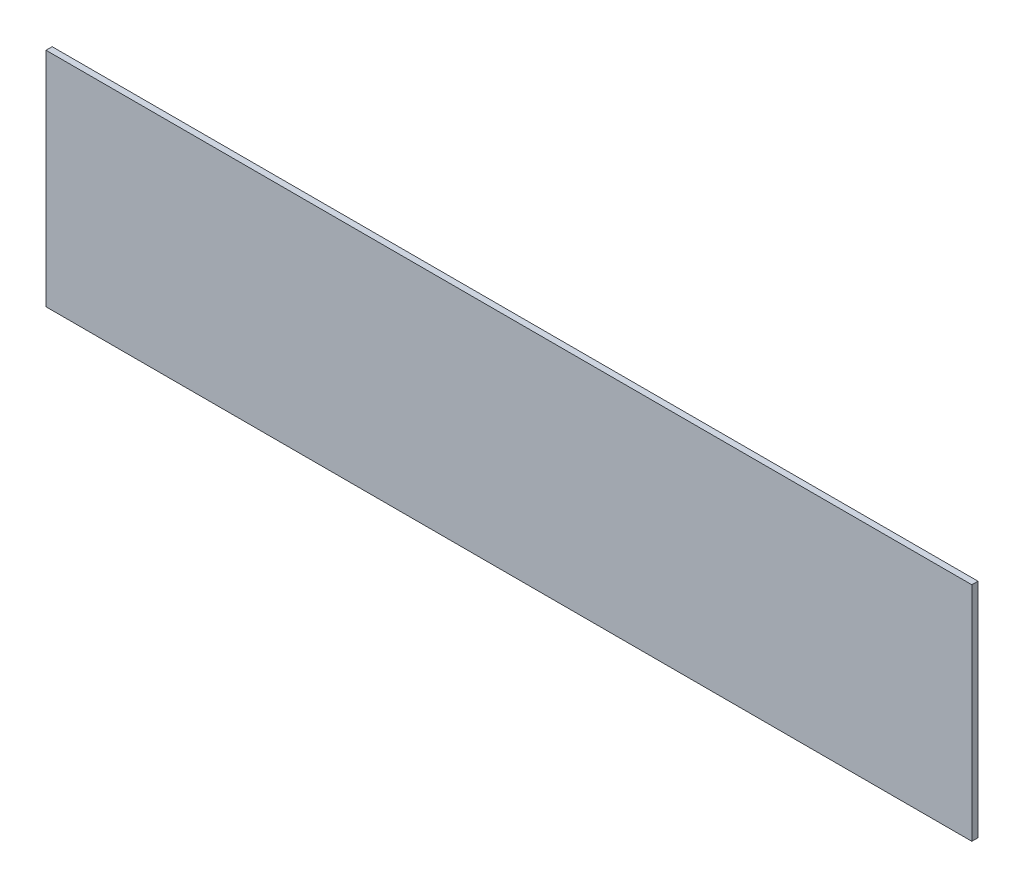
SolidWorks part; units mm, degrees
ref_plane "Front Plane" through (0, 0, 0) normal (0, 0, 1) x (1, 0, 0)
ref_plane "Top Plane" through (0, 0, 0) normal (0, 1, 0) x (1, 0, 0)
ref_plane "Right Plane" through (0, 0, 0) normal (1, 0, 0) x (0, 0, -1)
sketch "Sketch1" plane through (0, 0, 0) normal (0, 0, 1) x (1, 0, 0)
  line L1 (-90.3612, 53.3396) -> (385.8888, 53.3396)
  line L2 (-90.3612, 53.3396) -> (-90.3612, -60.9604)
  line L3 (-90.3612, -60.9604) -> (385.8888, -60.9604)
  line L4 (385.8888, 53.3396) -> (385.8888, -60.9604)
  dimension "D1" = 476.25
  dimension "D2" = 114.3
extrude "Boss-Extrude1" add sketch "Sketch1" along normal blind 3.175
